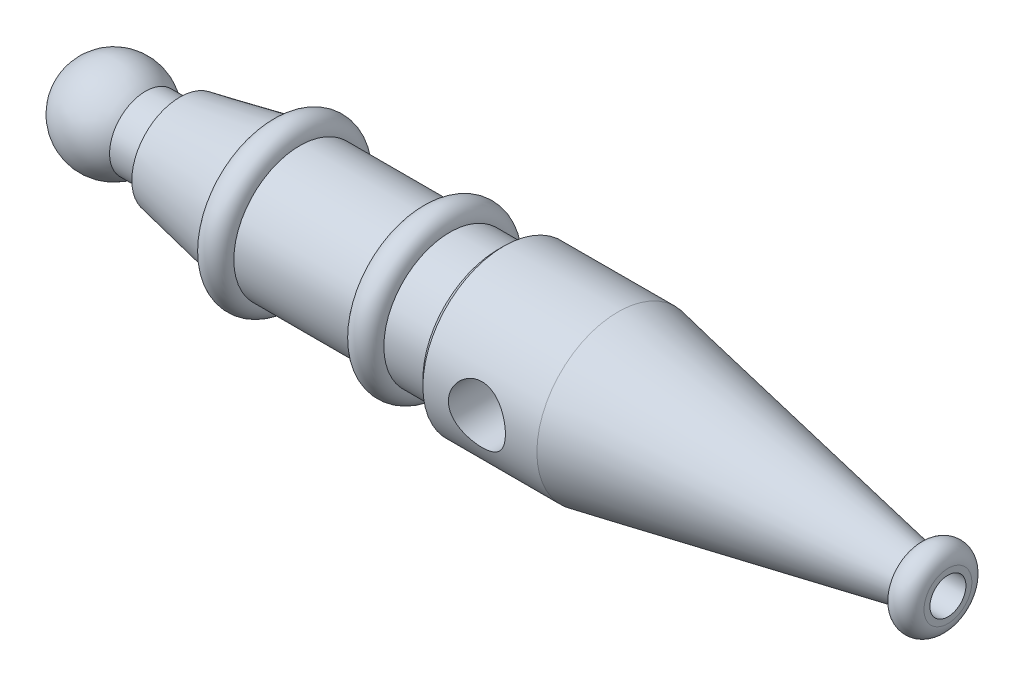
SolidWorks part; units mm, degrees
material "Plain Carbon Steel"
ref_plane "Front Plane" through (0, 0, 0) normal (0, 0, 1) x (1, 0, 0)
ref_plane "Top Plane" through (0, 0, 0) normal (0, 1, 0) x (1, 0, 0)
ref_plane "Right Plane" through (0, 0, 0) normal (1, 0, 0) x (0, 0, -1)
sketch "Sketch1" plane through (0, 0, 0) normal (0, 0, 1) x (1, 0, 0)
  line L0 (-91.8557, 0) -> (5.1443, 0)
  line L1 (-1091.8557, 0) -> (48908.1443, 0) construction
  line L2 (-78.5642, 6) -> (-72.8557, 6)
  line L3 (-72.8557, 6) -> (-72.8557, 8)
  line L4 (-52.8557, 11) -> (-32.8557, 11)
  line L5 (-27.8557, 11) -> (-19.8557, 11)
  line L6 (-57.8557, 11) -> (-72.8557, 8)
  line L7 (-19.8557, 11) -> (-19.8557, 13.5)
  line L8 (-19.8557, 13.5) -> (0.1443, 13.5)
  line L9 (0.1443, 13.5) -> (50.1443, 3.9852)
  line L10 (55.1443, 3) -> (5.1443, 3)
  line L11 (5.1443, 3) -> (5.1443, 0)
  line L12 (55.1443, 3) -> (55.1443, 3.9852)
  arc A0 (-78.5642, 6) -> (-91.8557, 0) centre (-83.8557, 0) ccw
  arc A1 (-57.8557, 11) -> (-52.8557, 11) centre (-55.3557, 11) cw
  arc A2 (-32.8557, 11) -> (-27.8557, 11) centre (-30.3557, 11) cw
  arc A3 (55.1443, 3.9852) -> (50.1443, 3.9852) centre (52.6443, 3.9852) ccw
  dimension "D2" = 20
  dimension "D7" = 2.5
  dimension "D6" = 8
  dimension "D4" = 2
  dimension "D5" = 20
  dimension "D10" = 50
revolve "Revolve1" add sketch "Sketch1" angle 360 about L1
chamfer "Chamfer1" distance 1 angle 45 1 edges at (-19.8557, 0, 13.5)
sketch "Sketch3" plane through (0, 0, 0) normal (0, 0, 1) x (1, 0, 0)
  circle A0 centre (-9.8557, 0) radius 4.75
  dimension "D2" = 9.5
extrude "Cut-Extrude1" cut sketch "Sketch3" against normal mid plane 40
